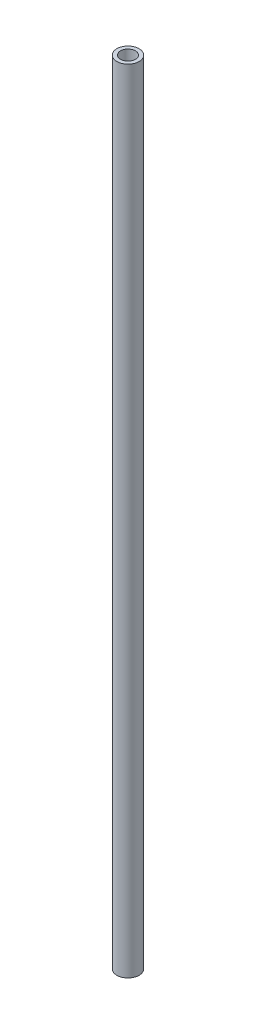
SolidWorks part; units mm, degrees
ref_plane "Front Plane" through (0, 0, 0) normal (0, 0, 1) x (1, 0, 0)
ref_plane "Top Plane" through (0, 0, 0) normal (0, 1, 0) x (1, 0, 0)
ref_plane "Right Plane" through (0, 0, 0) normal (1, 0, 0) x (0, 0, -1)
sketch "Sketch1" plane through (0, 0, 0) normal (0, 1, 0) x (1, 0, 0)
  circle A0 centre (0, 0) radius 2.25
  circle A1 centre (0, 0) radius 1.5
  dimension "D1" = 4.5
  dimension "D2" = 3
extrude "Boss-Extrude1" add sketch "Sketch1" along normal blind 160
